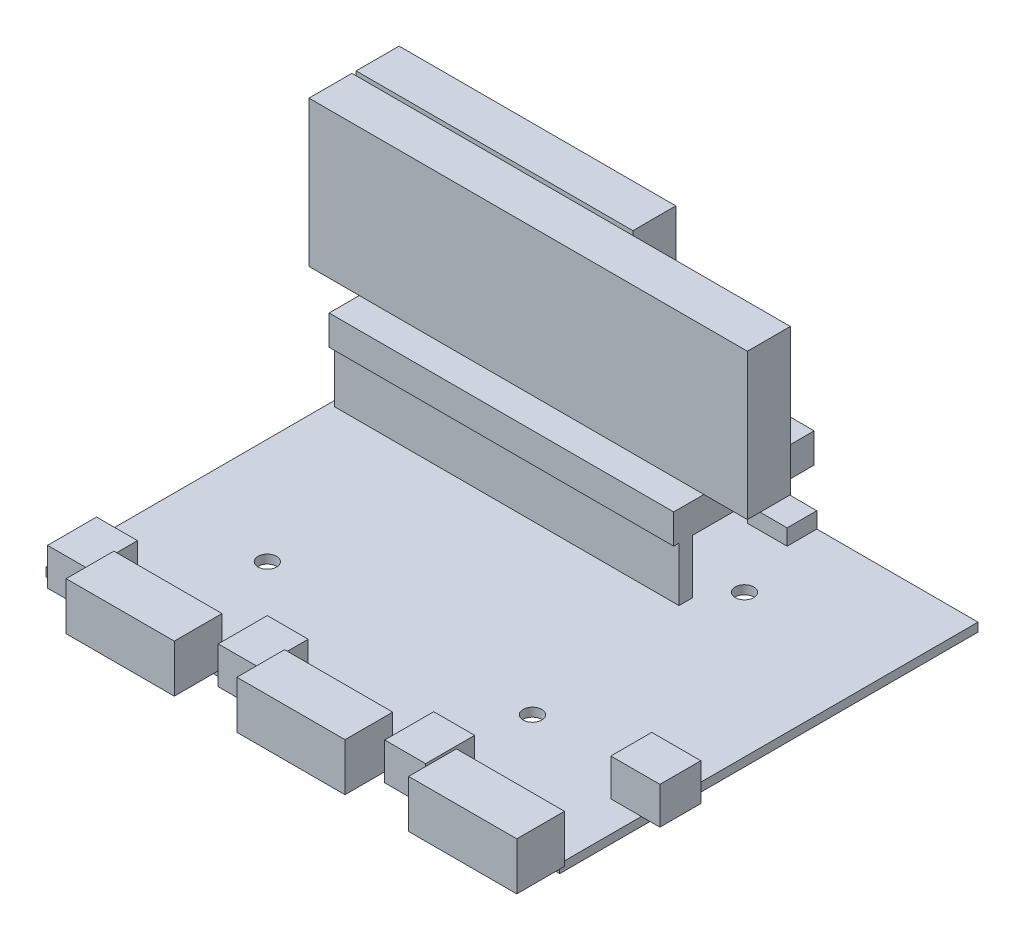
SolidWorks part; units mm, degrees
ref_plane "Front Plane" through (0, 0, 0) normal (0, 0, 1) x (1, 0, 0)
ref_plane "Top Plane" through (0, 0, 0) normal (0, 1, 0) x (1, 0, 0)
ref_plane "Right Plane" through (0, 0, 0) normal (1, 0, 0) x (0, 0, -1)
sketch "Sketch1" plane through (0, 0, 0) normal (0, 1, 0) x (1, 0, 0)
  line L1 (0, 0) -> (96.9, 0)
  line L2 (0, 0) -> (0, 78.9)
  line L3 (0, 78.9) -> (96.9, 78.9)
  line L4 (96.9, 0) -> (96.9, 78.9)
  dimension "D1" = 96.9
  dimension "D2" = 78.9
extrude "Boss-Extrude1" add sketch "Sketch1" along normal blind 1.64
sketch "Sketch2" plane through (0, 1.64, 0) normal (0, 1, 0) x (1, 0, 0)
  line L0 (35.8, 5.94) -> (43.52, 5.94)
  line L1 (0, 0) -> (96.9, 0) construction
  line L2 (3.6, 5.94) -> (11.32, 5.94)
  line L3 (3.6, 5.94) -> (3.6, -3.31)
  line L4 (3.6, -3.31) -> (11.32, -3.31)
  line L5 (11.32, 5.94) -> (11.32, -3.31)
  line L6 (0, 78.9) -> (0, 0) construction
  line L7 (35.8, 5.94) -> (35.8, -3.31)
  line L8 (35.8, -3.31) -> (43.52, -3.31)
  line L9 (43.52, 5.94) -> (43.52, -3.31)
  line L10 (67.2, 5.94) -> (74.92, 5.94)
  line L11 (67.2, 5.94) -> (67.2, -3.31)
  line L12 (67.2, -3.31) -> (74.92, -3.31)
  line L13 (74.92, 5.94) -> (74.92, -3.31)
  line L14 (91.14, 23.12) -> (100.4, 23.12)
  line L15 (91.14, 23.12) -> (91.14, 15.4)
  line L16 (91.14, 15.4) -> (100.4, 15.4)
  line L17 (100.4, 23.12) -> (100.4, 15.4)
  line L18 (96.9, 0) -> (96.9, 78.9) construction
  dimension "D1" = 9.25
  dimension "D2" = 7.72
  dimension "D3" = 3.31
  dimension "D4" = 3.6
  dimension "D5" = 9.25
  dimension "D6" = 7.72
  dimension "D7" = 9.25
  dimension "D8" = 7.72
  dimension "D9" = 35.8
  dimension "D10" = 67.2
  dimension "D11" = 9.26
  dimension "D12" = 7.72
  dimension "D13" = 15.4
  dimension "D14" = 3.5
extrude "Boss-Extrude2" add sketch "Sketch2" along normal blind 7
sketch "Sketch3" plane through (0, 1.64, 0) normal (0, 1, 0) x (1, 0, 0)
  line L0 (11.32, 0) -> (35.8, 0) construction
  line L1 (12.8, 0) -> (33.2, 0)
  line L2 (12.8, 0) -> (12.8, -9)
  line L3 (12.8, -9) -> (33.2, -9)
  line L4 (33.2, 0) -> (33.2, -9)
  line L5 (0, 78.9) -> (0, 0) construction
  line L6 (45, 0) -> (65.4, 0)
  line L7 (45, 0) -> (45, -9)
  line L8 (45, -9) -> (65.4, -9)
  line L9 (65.4, 0) -> (65.4, -9)
  line L10 (77.4, 0) -> (97.8, 0)
  line L11 (77.4, 0) -> (77.4, -9)
  line L12 (77.4, -9) -> (97.8, -9)
  line L13 (97.8, 0) -> (97.8, -9)
  dimension "D1" = 12.8
  dimension "D2" = 20.4
  dimension "D3" = 9
  dimension "D4" = 20.4
  dimension "D5" = 9
  dimension "D6" = 20.4
  dimension "D7" = 9
  dimension "D8" = 45
  dimension "D9" = 77.4
extrude "Boss-Extrude5" add sketch "Sketch3" along normal blind 9 separate body
sketch "Sketch4" plane through (0, 1.64, 0) normal (0, 1, 0) x (1, 0, 0)
  line L0 (96.9, 78.9) -> (0, 78.9) construction
  line L1 (59, 78.9) -> (66.5, 78.9)
  line L2 (59, 78.9) -> (59, 73.3)
  line L3 (59, 73.3) -> (66.5, 73.3)
  line L4 (66.5, 78.9) -> (66.5, 73.3)
  line L5 (0, 78.9) -> (0, 0) construction
  dimension "D1" = 59
  dimension "D2" = 7.5
  dimension "D3" = 5.6
extrude "Boss-Extrude6" add sketch "Sketch4" along normal blind 3
sketch "Sketch6" plane through (0, 1.64, 0) normal (0, 1, 0) x (1, 0, 0)
  line L0 (59, 78.9) -> (0, 78.9) construction
  line L1 (1, 78.9) -> (52.2, 78.9)
  line L2 (1, 78.9) -> (1, 76.4)
  line L3 (1, 76.4) -> (52.2, 76.4)
  line L4 (52.2, 78.9) -> (52.2, 76.4)
  line L5 (0, 78.9) -> (0, 0) construction
  line L7 (1, 53.4) -> (66, 53.4)
  line L8 (1, 53.4) -> (1, 55.9)
  line L9 (1, 55.9) -> (66, 55.9)
  line L10 (66, 53.4) -> (66, 55.9)
  dimension "D1" = 1
  dimension "D2" = 51.2
  dimension "D3" = 2.5
  dimension "D4" = 65
  dimension "D5" = 2.5
  dimension "D6" = 25.5
extrude "Boss-Extrude7" add sketch "Sketch6" along normal blind 10.2
sketch "Sketch7" plane through (0, 11.84, 0) normal (0, 1, 0) x (1, 0, 0)
  line L0 (1, 53.4) -> (66, 53.4) construction
  line L1 (1, 78.9) -> (66, 78.9)
  line L2 (1, 78.9) -> (1, 52.4)
  line L3 (1, 52.4) -> (66, 52.4)
  line L4 (66, 78.9) -> (66, 52.4)
  line L5 (52.2, 78.9) -> (1, 78.9) construction
  line L6 (1, 55.9) -> (1, 53.4) construction
  line L7 (66, 53.4) -> (66, 55.9) construction
  dimension "D1" = 1
extrude "Boss-Extrude8" add sketch "Sketch7" along normal blind 5.6
sketch "Sketch8" plane through (0, 17.44, 0) normal (0, 1, 0) x (1, 0, 0)
  line L0 (66, 78.9) -> (1, 78.9) construction
  line L1 (43.7, 75.1) -> (-8.5, 75.1)
  line L2 (43.7, 75.1) -> (43.7, 67)
  line L3 (43.7, 67) -> (-8.5, 67)
  line L4 (-8.5, 75.1) -> (-8.5, 67)
  line L5 (74.2, 66.2) -> (-8.5, 66.2)
  line L6 (74.2, 66.2) -> (74.2, 58.1)
  line L7 (74.2, 58.1) -> (-8.5, 58.1)
  line L8 (-8.5, 66.2) -> (-8.5, 58.1)
  line L9 (1, 52.4) -> (66, 52.4) construction
  line L10 (1, 78.9) -> (1, 52.4) construction
  dimension "D1" = 52.2
  dimension "D2" = 82.7
  dimension "D3" = 8.1
  dimension "D4" = 8.1
  dimension "D5" = 3.8
  dimension "D6" = 5.7
  dimension "D7" = 9.5
extrude "Boss-Extrude9" add sketch "Sketch8" along normal blind 27.5
sketch "Sketch10" plane through (0, 0, 0) normal (0, -1, 0) x (1, 0, 0)
  line L0 (0, -78.9) -> (0, 0) construction
  line L1 (0, 0) -> (96.9, 0) construction
  circle A0 centre (20, -21.75) radius 1.75
  circle A1 centre (70, -21.75) radius 1.75
  circle A2 centre (20, -61.75) radius 1.75
  circle A3 centre (70, -61.75) radius 1.75
  dimension "D6" = 3.5
  dimension "D1" = 20
  dimension "D2" = 21.75
  dimension "D3" = 21.75
  dimension "D4" = 50
  dimension "D5" = 40
extrude "Cut-Extrude1" cut sketch "Sketch10" against normal blind 2
